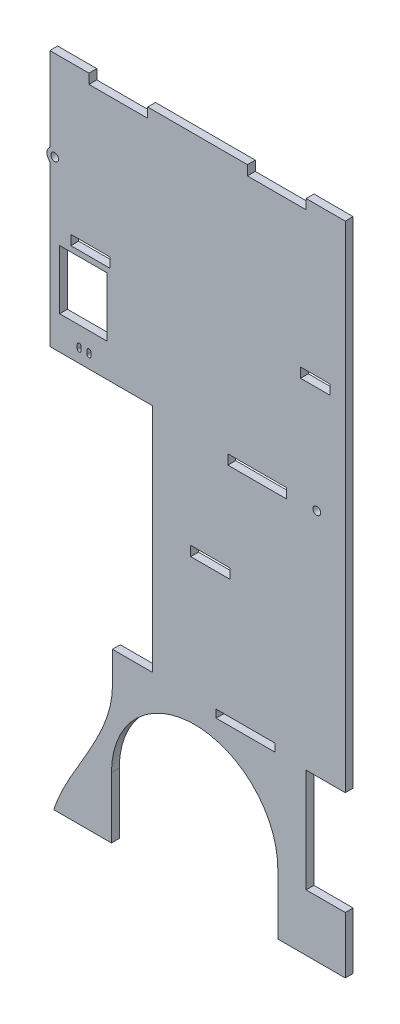
SolidWorks part; units mm, degrees
ref_plane "Front Plane" through (0, 0, 0) normal (0, 0, 1) x (1, 0, 0)
ref_plane "Top Plane" through (0, 0, 0) normal (0, 1, 0) x (1, 0, 0)
ref_plane "Right Plane" through (0, 0, 0) normal (1, 0, 0) x (0, 0, -1)
sketch "Sketch1" plane through (0, 0, 0) normal (0, 0, 1) x (1, 0, 0)
  line L1 (-75.5, 125.5) -> (75.5, 125.5)
  line L2 (-75.5, 125.5) -> (-75.5, -127.5)
  line L3 (-75.5, -127.5) -> (75.5, -127.5)
  line L4 (75.5, 125.5) -> (75.5, -127.5)
  dimension "D1" = 151
  dimension "D2" = 253
  dimension "D3" = 75.5
  dimension "D4" = 127.5
extrude "Boss-Extrude1" add sketch "Sketch1" along normal blind 4
sketch "Sketch2" plane through (0, 0, 4) normal (0, 0, 1) x (1, 0, 0)
  line L0 (-75.5, -5.4971) -> (-22.9969, -5.4971)
  line L1 (-75.5, -5.4971) -> (-75.5, -127.5)
  line L2 (-75.5, -127.5) -> (-22.9969, -127.5)
  line L3 (-22.9969, -5.4971) -> (-22.9969, -127.5)
  line L4 (-75.5, -127.5) -> (75.5, -127.5) construction
  line L7 (-75.5, 125.5) -> (-75.5, -127.5) construction
  dimension "D1" = 52.5031
  dimension "D2" = 122.0029
extrude "Cut-Extrude1" cut sketch "Sketch2" against normal blind 5
sketch "Sketch3" plane through (0, 0, 4) normal (0, 0, 1) x (1, 0, 0)
  line L0 (-40.45, 125.5) -> (-40.45, 120.4) construction
  line L1 (40.55, 125.5) -> (40.55, 120.4) construction
  line L4 (30.55, -7.5) -> (30.55, -12.6) construction
  line L5 (6.55, -57.5) -> (6.55, -62.6) construction
  line L6 (24.55, -123.4) -> (24.55, -127.5) construction
  line L7 (-55.5, 122.95) -> (-25.4, 122.95) construction
  line L8 (-25.4, 125.5) -> (-55.5, 125.5)
  line L9 (-55.5, 125.5) -> (-55.5, 120.4)
  line L10 (-55.5, 120.4) -> (-25.4, 120.4)
  line L11 (-25.4, 120.4) -> (-25.4, 125.5)
  line L12 (25.5, 122.95) -> (55.6, 122.95) construction
  line L15 (15.5, -10.05) -> (45.6, -10.05) construction
  line L16 (55.6, 125.5) -> (25.5, 125.5)
  line L17 (25.5, 125.5) -> (25.5, 120.4)
  line L18 (25.5, 120.4) -> (55.6, 120.4)
  line L19 (55.6, 120.4) -> (55.6, 125.5)
  line L20 (-3.5, -60.05) -> (16.6, -60.05) construction
  line L21 (9.5, -125.45) -> (39.6, -125.45) construction
  line L22 (75.5, 125.5) -> (-75.5, 125.5) construction
  line L29 (15.5, -7.5) -> (45.5, -7.5) construction
  line L30 (-3.5, -57.5) -> (16.5, -57.5) construction
  line L40 (45.6, -7.5) -> (15.5, -7.5)
  line L41 (15.5, -7.5) -> (15.5, -12.6)
  line L42 (15.5, -12.6) -> (45.6, -12.6)
  line L43 (45.6, -12.6) -> (45.6, -7.5)
  line L48 (16.6, -57.5) -> (-3.5, -57.5)
  line L49 (-3.5, -57.5) -> (-3.5, -62.6)
  line L50 (-3.5, -62.6) -> (16.6, -62.6)
  line L51 (16.6, -62.6) -> (16.6, -57.5)
  line L56 (39.6, -123.4) -> (9.5, -123.4)
  line L57 (9.5, -123.4) -> (9.5, -127.5)
  line L58 (9.5, -127.5) -> (39.6, -127.5)
  line L59 (39.6, -127.5) -> (39.6, -123.4)
  dimension "D1" = 15.05
  dimension "D2" = 15.05
  dimension "D5" = 15.05
  dimension "D6" = 10.05
  dimension "D7" = 15.05
  dimension "D8" = 2.55
  dimension "D9" = 5.1
  dimension "D12" = 5.1
  dimension "D13" = 5.1
  dimension "D14" = 4.1
extrude "Cut-Extrude2" [suppressed] cut sketch "Sketch3" against normal blind 5
sketch "Sketch4" plane through (0, 0, 4) normal (0, 0, 1) x (1, 0, 0)
  line L8 (67.675, 51.5) -> (52.675, 51.5)
  line L9 (52.675, 51.5) -> (52.675, 46.5)
  line L10 (52.675, 46.5) -> (67.675, 46.5)
  line L11 (67.675, 46.5) -> (67.675, 51.5)
  line L16 (-44.75, 51.5) -> (-64.75, 51.5)
  line L17 (-64.75, 51.5) -> (-64.75, 46.5)
  line L18 (-64.75, 46.5) -> (-44.75, 46.5)
  line L19 (-44.75, 46.5) -> (-44.75, 51.5)
extrude "Cut-Extrude3" [suppressed] cut sketch "Sketch4" against normal blind 10
sketch "Sketch5" plane through (0, 0, 4) normal (0, 0, 1) x (1, 0, 0)
  line L0 (-22.9969, -5.4971) -> (-75.5, -5.4971) construction
  line L1 (-75.5, 125.5) -> (-75.5, -5.4971) construction
  line L2 (-60.5, 0.5029) -> (-60.5, 2.5029) construction
  line L3 (-61.5, 0.5029) -> (-61.5, 2.5029)
  line L4 (-59.5, 0.5029) -> (-59.5, 2.5029)
  line L5 (-55.5, 0.5029) -> (-55.5, 2.5029) construction
  line L6 (-56.5, 0.5029) -> (-56.5, 2.5029)
  line L7 (-54.5, 0.5029) -> (-54.5, 2.5029)
  arc A2 (-61.5, 0.5029) -> (-59.5, 0.5029) centre (-60.5, 0.5029) ccw
  arc A3 (-59.5, 2.5029) -> (-61.5, 2.5029) centre (-60.5, 2.5029) ccw
  arc A4 (-56.5, 0.5029) -> (-54.5, 0.5029) centre (-55.5, 0.5029) ccw
  arc A5 (-54.5, 2.5029) -> (-56.5, 2.5029) centre (-55.5, 2.5029) ccw
  point P6 (-60.5, 1.5029)
  point P14 (-55.5, 1.5029)
  dimension "D1" = 2
  dimension "D2" = 2
  dimension "D3" = 6
  dimension "D4" = 5
  dimension "D5" = 15
extrude "Cut-Extrude4" cut sketch "Sketch5" against normal blind 5
sketch "Sketch8" plane through (0, 0, 4) normal (0, 0, 1) x (1, 0, 0)
  circle A0 centre (-73, 79.5622) radius 2
  dimension "D1" = 4
extrude "Cut-Extrude6" cut sketch "Sketch8" against normal blind 5
sketch "Sketch10" plane through (0, 0, 4) normal (0, 0, 1) x (1, 0, 0)
  circle A0 centre (-73, 79.5622) radius 2
  circle A1 centre (-73, 79.5622) radius 4
  dimension "D1" = 8
extrude "Boss-Extrude3" add sketch "Sketch10" against normal blind 4
sketch "Sketch11" plane through (0, 0, 0) normal (0, 0, -1) x (-1, 0, 0)
  line L0 (75.5, 76.4397) -> (75.5, -5.4971) construction
  line L1 (22.9969, -5.4971) -> (75.5, -5.4971) construction
  line L8 (70.5, 11.5) -> (70.5, 41.7)
  line L9 (70.5, 41.7) -> (46.3, 41.7)
  line L10 (46.3, 41.7) -> (46.3, 11.5)
  line L11 (46.3, 11.5) -> (70.5, 11.5)
  dimension "D1" = 5
  dimension "D2" = 16.9971
  dimension "D3" = 24.2
  dimension "D4" = 30.2
extrude "Cut-Extrude9" cut sketch "Sketch11" against normal blind 10
sketch "Sketch14" plane through (0, 0, 4) normal (0, 0, 1) x (1, 0, 0)
  line L8 (-44.75, 45.5) -> (-44.75, 50.5)
  line L9 (-64.75, 45.5) -> (-44.75, 45.5)
  line L10 (-64.75, 45.5) -> (-64.75, 50.5)
  line L11 (-64.75, 50.5) -> (-44.75, 50.5)
  line L12 (52.675, 45.5) -> (67.675, 45.5)
  line L13 (52.675, 45.5) -> (52.675, 50.5)
  line L14 (52.675, 50.5) -> (67.675, 50.5)
  line L15 (67.675, 45.5) -> (67.675, 50.5)
extrude "Cut-Extrude10" [suppressed] cut sketch "Sketch14" against normal blind 10
sketch "Sketch16" plane through (0, 0, 4) normal (0, 0, 1) x (1, 0, 0)
  line L0 (75.5, -127.5) -> (75.5, 125.5) construction
  line L1 (-43.4969, -127.5) -> (75.5, -127.5)
  line L2 (-43.4969, -127.5) -> (-43.4969, -209.5)
  line L3 (-43.4969, -209.5) -> (75.5, -209.5)
  line L4 (75.5, -127.5) -> (75.5, -209.5)
  dimension "D1" = 82
  dimension "D2" = 118.9969
extrude "Boss-Extrude4" add sketch "Sketch16" against normal blind 4
sketch "Sketch24" plane through (0, 0, 4) normal (0, 0, 1) x (1, 0, 0)
  line L0 (-43.4969, -138.7176) -> (-43.4969, -209.5)
  line L1 (-73.5, -209.5) -> (-43.4969, -209.5)
  spline S2 degree 3 poles (-73.5, -209.5) (-66.4121, -186.7217) (-43.0426, -163.1595) (-43.4969, -138.7176) knots 0 0 0 0 0.867945 0.867945 0.867945 0.867945
extrude "Boss-Extrude5" add sketch "Sketch24" against normal blind 4
sketch "Sketch26" plane through (0, 0, 4) normal (0, 0, 1) x (1, 0, 0)
  line L0 (-1.5, -187.3) -> (-1.5, -135.5839) construction
  line L1 (-12.7774, -178.3) -> (19.0653, -178.3) construction
  line L2 (-44, -178.3) -> (-44, -209.5)
  line L3 (-73.5, -209.5) -> (75.5, -209.5) construction
  line L4 (41, -178.3) -> (41, -209.5)
  line L5 (-44, -209.5) -> (41, -209.5)
  arc A3 (41, -178.3) -> (-44, -178.3) centre (-1.5, -178.3) ccw
  dimension "D2" = 85
  dimension "D1" = 9
extrude "Cut-Extrude13" cut sketch "Sketch26" against normal blind 10 contours L5 L4 A3 L2
sketch "Sketch27" plane through (0, 0, 4) normal (0, 0, 1) x (1, 0, 0)
  line L0 (75.5, -209.5) -> (75.5, 125.5) construction
  line L1 (75.5, -127.5) -> (55.5, -127.5)
  line L2 (75.5, -127.5) -> (75.5, -180.5)
  line L3 (75.5, -180.5) -> (55.5, -180.5)
  line L4 (55.5, -127.5) -> (55.5, -180.5)
  line L5 (-22.9969, -127.5) -> (-43.4969, -127.5) construction
  dimension "D1" = 20
  dimension "D2" = 53
extrude "Cut-Extrude14" cut sketch "Sketch27" against normal blind 5
sketch "Sketch28" plane through (0, 0, 4) normal (0, 0, 1) x (1, 0, 0)
  line L0 (41, -178.3) -> (41, -209.5) construction
  line L1 (41, -178.3) -> (41, -209.5)
  line L2 (40.1493, -169.8391) -> (55.5, -169.8391)
  line L3 (55.5, -127.5) -> (55.5, -180.5) construction
  line L4 (55.5, -169.8391) -> (55.5, -180.5)
  line L5 (55.5, -180.5) -> (75.5, -180.5) construction
  line L6 (55.5, -180.5) -> (75.5, -180.5)
  line L7 (75.5, -209.5) -> (75.5, -180.5) construction
  line L8 (75.5, -209.5) -> (75.5, -180.5)
  line L9 (41, -209.5) -> (75.5, -209.5) construction
  line L10 (41, -209.5) -> (75.5, -209.5)
  arc A0 (41, -178.3) -> (-44, -178.3) centre (-1.5, -178.3) ccw construction
  arc A1 (41, -178.3) -> (40.1493, -169.8391) centre (-1.5, -178.3) ccw
extrude "Cut-Extrude15" [suppressed] cut sketch "Sketch28" against normal blind 10
sketch "Sketch29" plane through (0, 0, 4) normal (0, 0, 1) x (1, 0, 0)
  line L1 (-43.4969, -127.5) -> (-22.9969, -127.5)
  line L2 (-43.4969, -127.5) -> (-43.4969, -123.5)
  line L3 (-43.4969, -123.5) -> (-22.9969, -123.5)
  line L4 (-22.9969, -127.5) -> (-22.9969, -123.5)
extrude "Boss-Extrude6" add sketch "Sketch29" against normal blind 4
sketch "Sketch31" plane through (0, 0, 4) normal (0, 0, 1) x (1, 0, 0)
  line L1 (25.5, 125.5) -> (55.5, 125.5)
  line L2 (25.5, 125.5) -> (25.5, 120.5)
  line L3 (25.5, 120.5) -> (55.5, 120.5)
  line L4 (55.5, 125.5) -> (55.5, 120.5)
  line L5 (-55.5, 125.5) -> (-25.5, 125.5)
  line L6 (-55.5, 125.5) -> (-55.5, 120.5)
  line L7 (-55.5, 120.5) -> (-25.5, 120.5)
  line L8 (-25.5, 125.5) -> (-25.5, 120.5)
  line L11 (52.6363, 49.5) -> (67.675, 49.5)
  line L12 (52.6363, 49.5) -> (52.6363, 44.5)
  line L13 (52.6363, 44.5) -> (67.675, 44.5)
  line L14 (67.675, 49.5) -> (67.675, 44.5)
  line L15 (15.5, -7.5) -> (45.5, -7.5)
  line L16 (15.5, -7.5) -> (15.5, -12.5)
  line L17 (15.5, -12.5) -> (45.5, -12.5)
  line L18 (45.5, -7.5) -> (45.5, -12.5)
  line L19 (-3.5, -57.5) -> (16.5, -57.5)
  line L20 (-3.5, -57.5) -> (-3.5, -62.5)
  line L21 (-3.5, -62.5) -> (16.5, -62.5)
  line L22 (16.5, -57.5) -> (16.5, -62.5)
  line L23 (-64.75, 49.5) -> (-44.75, 49.5)
  line L24 (-64.75, 49.5) -> (-64.75, 44.5)
  line L25 (-64.75, 44.5) -> (-44.75, 44.5)
  line L26 (-44.75, 49.5) -> (-44.75, 44.5)
  line L27 (9.5, -123.5) -> (39.5, -123.5)
  line L28 (9.5, -123.5) -> (9.5, -127.5)
  line L29 (9.5, -127.5) -> (39.5, -127.5)
  line L30 (39.5, -123.5) -> (39.5, -127.5)
  point P11 (0, 0)
  point P12 (0, 0)
  point P13 (0, 0)
extrude "Cut-Extrude16" cut sketch "Sketch31" against normal blind 10
sketch "Sketch32" plane through (0, 0, 4) normal (0, 0, 1) x (1, 0, 0)
  circle A0 centre (60.9367, -10) radius 2
  dimension "D1" = 4
extrude "Cut-Extrude17" cut sketch "Sketch32" against normal blind 10
